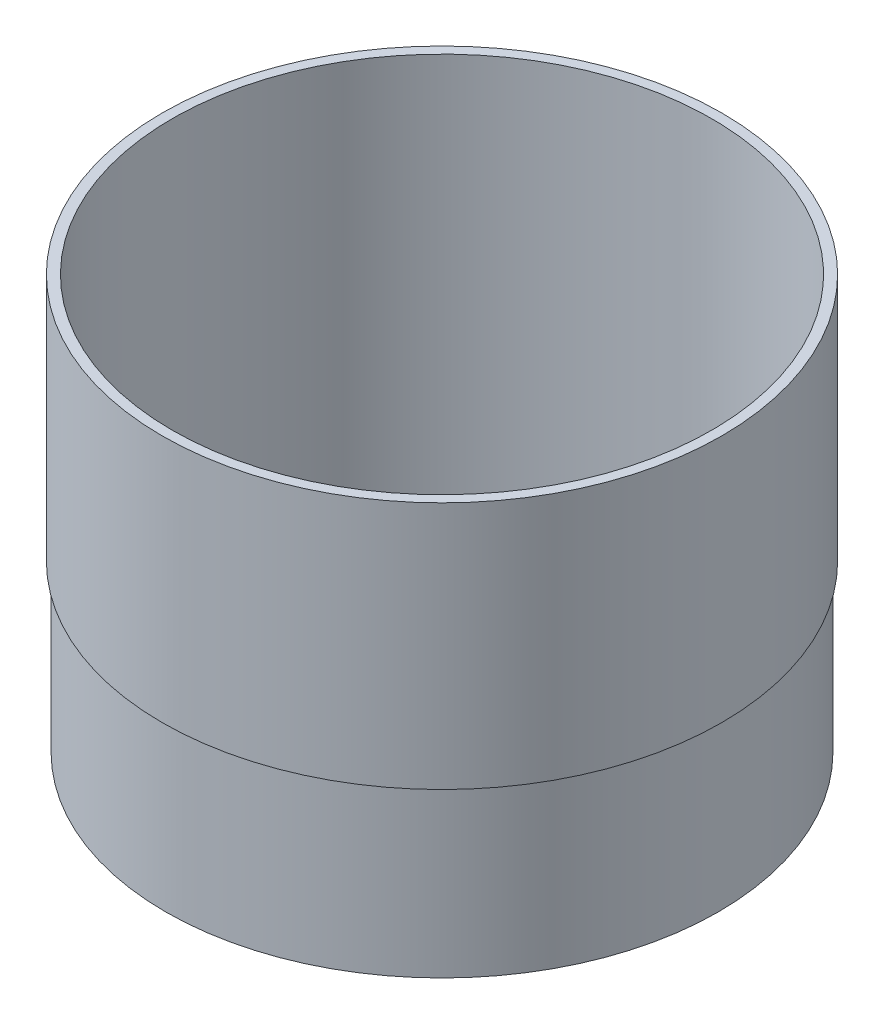
SolidWorks part; units mm, degrees
ref_plane "Front Plane" through (0, 0, 0) normal (0, 0, 1) x (1, 0, 0)
ref_plane "Top Plane" through (0, 0, 0) normal (0, 1, 0) x (1, 0, 0)
ref_plane "Right Plane" through (0, 0, 0) normal (1, 0, 0) x (0, 0, -1)
sketch "Sketch1" plane through (0, 0, 0) normal (0, 1, 0) x (1, 0, 0)
  circle A0 centre (0, 0) radius 16.7
  circle A1 centre (0, 0) radius 16.3
  dimension "D1" = 33.4
  dimension "D2" = 32.6
extrude "Boss-Extrude1" add sketch "Sketch1" along normal blind 10
sketch "Sketch2" plane through (0, 10, 0) normal (0, 1, 0) x (1, 0, 0)
  circle A0 centre (0, 0) radius 16.9
  circle A1 centre (0, 0) radius 16.3
  dimension "D1" = 33.8
  dimension "D2" = 32.6
extrude "Boss-Extrude2" add sketch "Sketch2" along normal blind 15
